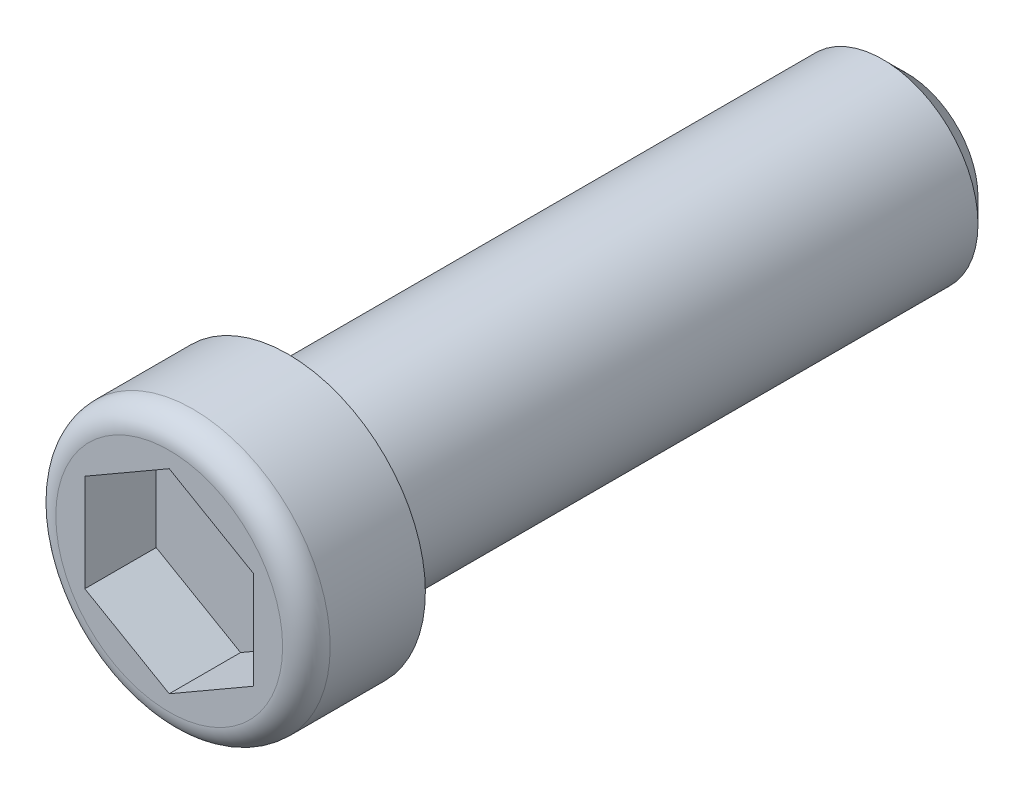
SolidWorks part; units mm, degrees
ref_plane "前视基准面" through (0, 0, 0) normal (0, 0, 1) x (1, 0, 0)
ref_plane "上视基准面" through (0, 0, 0) normal (0, 1, 0) x (1, 0, 0)
ref_plane "右视基准面" through (0, 0, 0) normal (1, 0, 0) x (0, 0, -1)
sketch "草图1" plane through (0, 0, 0) normal (0, 0, 1) x (1, 0, 0)
  circle A0 centre (0, 0) radius 2
extrude "凸台-拉伸1" add sketch "草图1" along normal blind 13
sketch "草图2" plane through (0, 0, 13) normal (0, 0, 1) x (1, 0, 0)
  circle A0 centre (0, 0) radius 2.8838
extrude "凸台-拉伸2" add sketch "草图2" along normal blind 2.5
sketch "草图3" plane through (0, 0, 15.5) normal (0, 0, 1) x (1, 0, 0)
  line L1 (0, 2.0484) -> (-1.774, 1.0242)
  line L2 (-1.774, 1.0242) -> (-1.774, -1.0242)
  line L3 (-1.774, -1.0242) -> (0, -2.0484)
  line L4 (0, -2.0484) -> (1.774, -1.0242)
  line L5 (1.774, -1.0242) -> (1.774, 1.0242)
  line L6 (1.774, 1.0242) -> (0, 2.0484)
  circle A0 centre (0, 0) radius 1.774 construction
extrude "切除-拉伸1" cut sketch "草图3" against normal blind 1.5
chamfer "倒角1" distance 0.5 angle 45 1 edges at (2, 0, 0)
fillet "圆角1" radius 0.5 1 edges at (2.8838, 0, 15.5)
